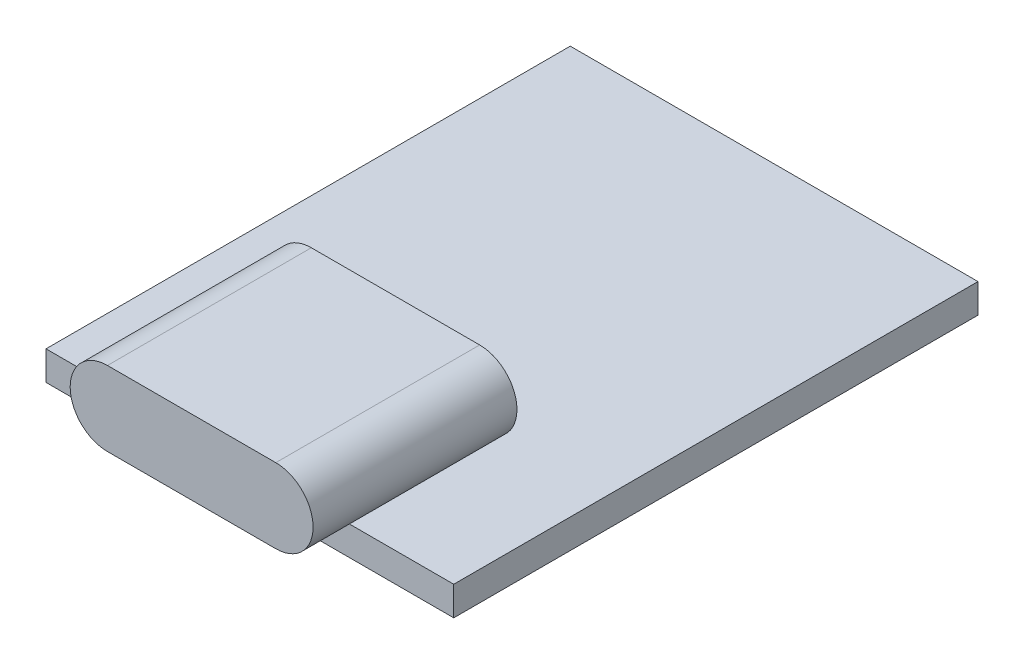
SolidWorks part; units mm, degrees
ref_plane "Front Plane" through (0, 0, 0) normal (0, 0, 1) x (1, 0, 0)
ref_plane "Top Plane" through (0, 0, 0) normal (0, 1, 0) x (1, 0, 0)
ref_plane "Right Plane" through (0, 0, 0) normal (1, 0, 0) x (0, 0, -1)
sketch "Sketch1" plane through (0, 0, 0) normal (0, 1, 0) x (1, 0, 0)
  line L1 (0, 0) -> (14, 0)
  line L2 (0, 0) -> (0, -18)
  line L3 (0, -18) -> (14, -18)
  line L4 (14, 0) -> (14, -18)
  dimension "D1" = 18
  dimension "D2" = 14
extrude "Boss-Extrude1" add sketch "Sketch1" along normal blind 1
sketch "Sketch2" plane through (0, 0, 18) normal (0, 0, 1) x (1, 0, 0)
  line L1 (4.11, 3.56) -> (9.89, 3.56)
  line L2 (4.11, 3.56) -> (4.11, 1)
  line L3 (4.11, 1) -> (9.89, 1)
  line L4 (9.89, 3.56) -> (9.89, 1)
  line L7 (0, 1) -> (14, 1) construction
  line L8 (7, -2.3669) -> (7, 2.3669) construction
  line L9 (0, 0) -> (14, 0) construction
  arc A0 (4.11, 3.56) -> (4.11, 1) centre (4.11, 2.28) ccw
  arc A1 (9.89, 3.56) -> (9.89, 1) centre (9.89, 2.28) cw
  point P14 (7, 0)
  line M9 (14, 1) -> (0, 1)
  dimension "D2" = 5.78
  dimension "D1" = 2.56
extrude "Boss-Extrude2" add sketch "Sketch2" along normal blind 2 and the other way blind 5 contours L2 A0 | L4 L1 L2 M9 | A1 L4
sketch "Sketch3" plane through (0, 1, 0) normal (0, 1, 0) x (1, 0, 0)
  line L0 (7, 0) -> (7, -30.1435) construction
  line L1 (14, 0) -> (0, 0) construction
sketch "Sketch4" plane through (0, 0, 0) normal (0, 0, -1) x (-1, 0, 0)
  line L0 (-7, 1) -> (-7, -5.1168) construction
  line L1 (-9.89, 1) -> (-4.11, 1) construction
ref_plane "Plane1" through (7, 0, 0) normal (1, 0, 0) x (0, 0, -1)
